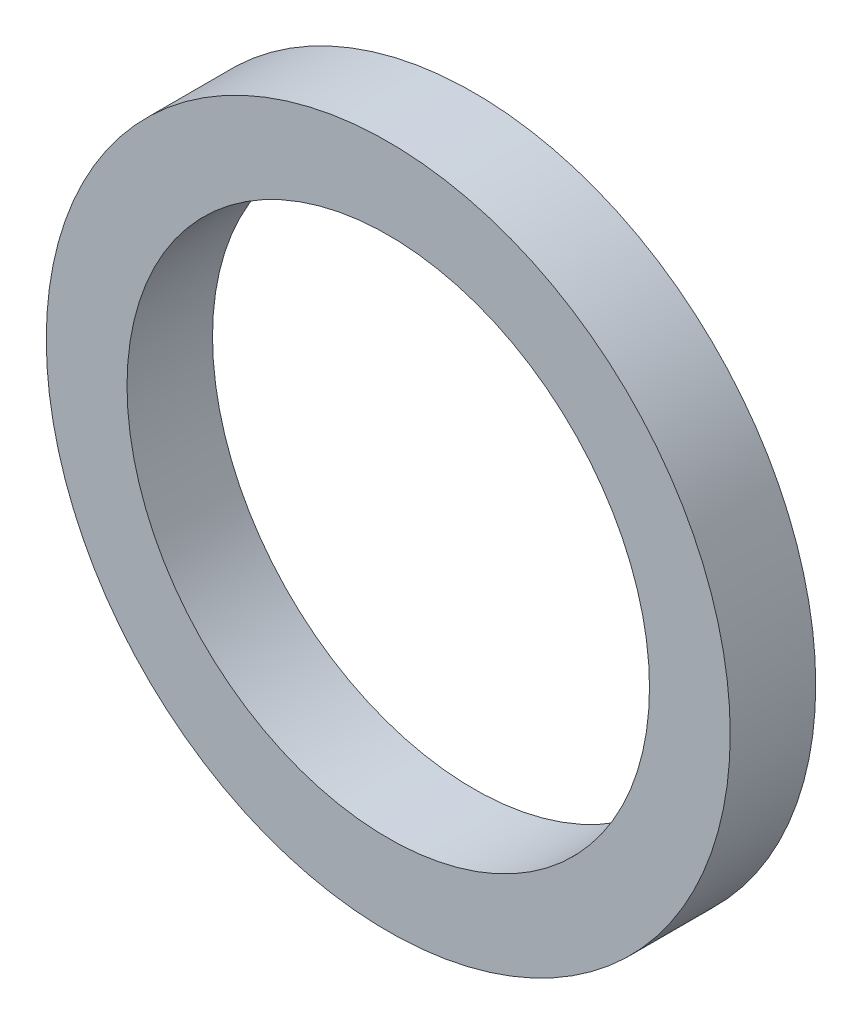
SolidWorks part; units mm, degrees
ref_plane "Спереди" through (0, 0, 0) normal (0, 0, 1) x (1, 0, 0)
ref_plane "Сверху" through (0, 0, 0) normal (0, 1, 0) x (1, 0, 0)
ref_plane "Справа" through (0, 0, 0) normal (1, 0, 0) x (0, 0, -1)
sketch "Эскиз1" plane through (0, 0, 0) normal (0, 0, 1) x (1, 0, 0)
  circle A0 centre (0, 0) radius 27.5
  circle A1 centre (0, 0) radius 36
  dimension "D1" = 72
  dimension "D2" = 55
extrude "Бобышка-Вытянуть1" add sketch "Эскиз1" along normal blind 9
